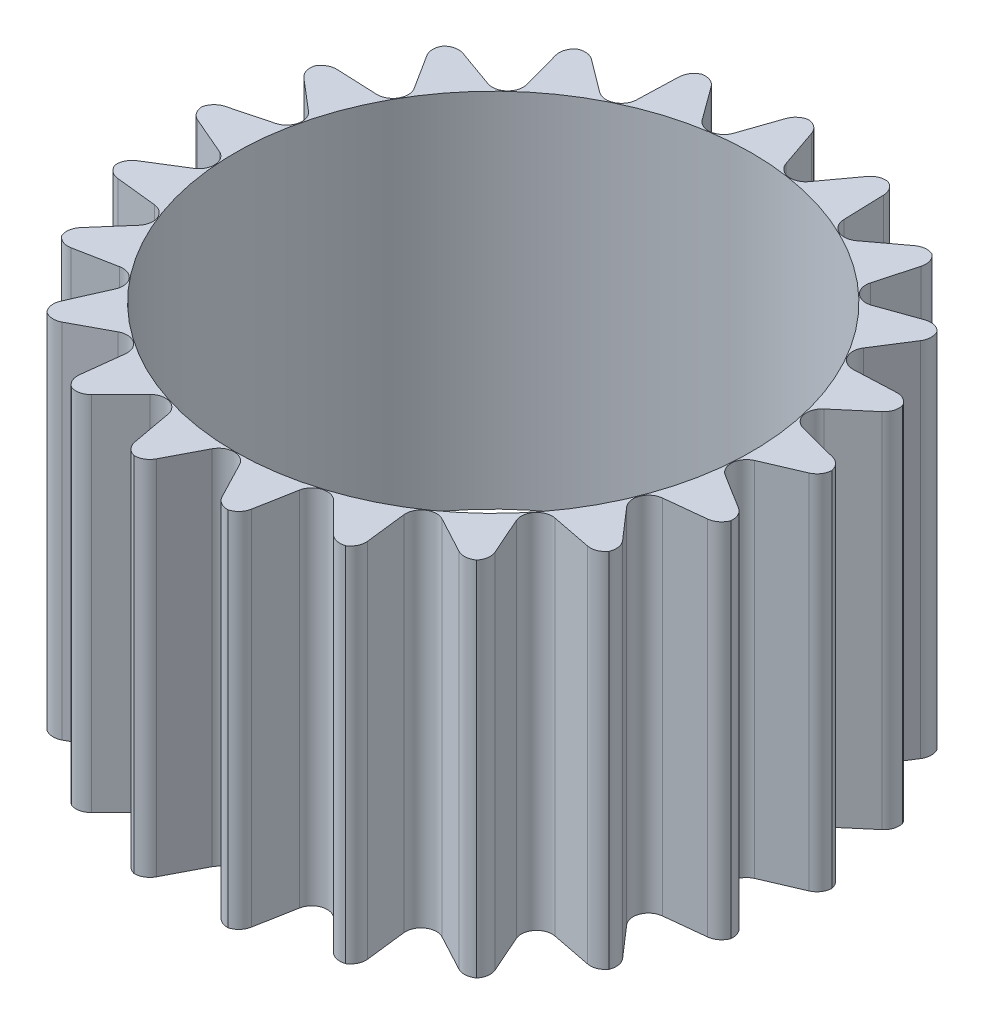
SolidWorks part; units mm, degrees
material "1060 Alloy"
ref_plane "Front Plane" through (0, 0, 0) normal (0, 0, 1) x (1, 0, 0)
ref_plane "Top Plane" through (0, 0, 0) normal (0, 1, 0) x (1, 0, 0)
ref_plane "Right Plane" through (0, 0, 0) normal (1, 0, 0) x (0, 0, -1)
sketch "Sketch1" plane through (0, 0, 0) normal (0, 1, 0) x (1, 0, 0)
  circle A0 centre (0, 0) radius 5
  circle A1 centre (0, 0) radius 6.11
  dimension "D1" = 10
  dimension "D2" = 12.22
extrude "Boss-Extrude1" add sketch "Sketch1" along normal blind 7
sketch "Sketch2" plane through (0, 0, 0) normal (0, 1, 0) x (1, 0, 0)
  line L0 (0, 0) -> (0, -6.11) construction
  line L1 (0, -5.31) -> (-0.9009, -5.7397) construction
  line L2 (0, -5.31) -> (0.9009, -5.7397) construction
  line L3 (0.635, -5.8785) -> (0.266, -5.1712)
  line L5 (-0.635, -5.8785) -> (-0.266, -5.1712)
  circle A0 centre (0, 0) radius 6.11 construction
  circle A1 centre (0, -5.31) radius 0.3 construction
  circle A2 centre (-0.9009, -5.7397) radius 0.3 construction
  circle A3 centre (0.9009, -5.7397) radius 0.3 construction
  arc A4 (-0.635, -5.8785) -> (-0.9475, -6.0361) centre (-0.9009, -5.7397) cw
  arc A5 (0.635, -5.8785) -> (0.9475, -6.0361) centre (0.9009, -5.7397) ccw
  arc A6 (0.266, -5.1712) -> (-0.266, -5.1712) centre (0, -5.31) ccw
  arc A7 (-0.9475, -6.0361) -> (0.9475, -6.0361) centre (0, -6.11) ccw
  dimension "D2" = 0.6
  dimension "D3" = 129
  dimension "D1" = 0.8
extrude "Cut-Extrude2" cut sketch "Sketch2" along normal up to next
pattern_circular "CirPattern1" count 21 every 17.143 about axis through (0, 0, 0) along (0, 1, 0) of "Cut-Extrude2"
